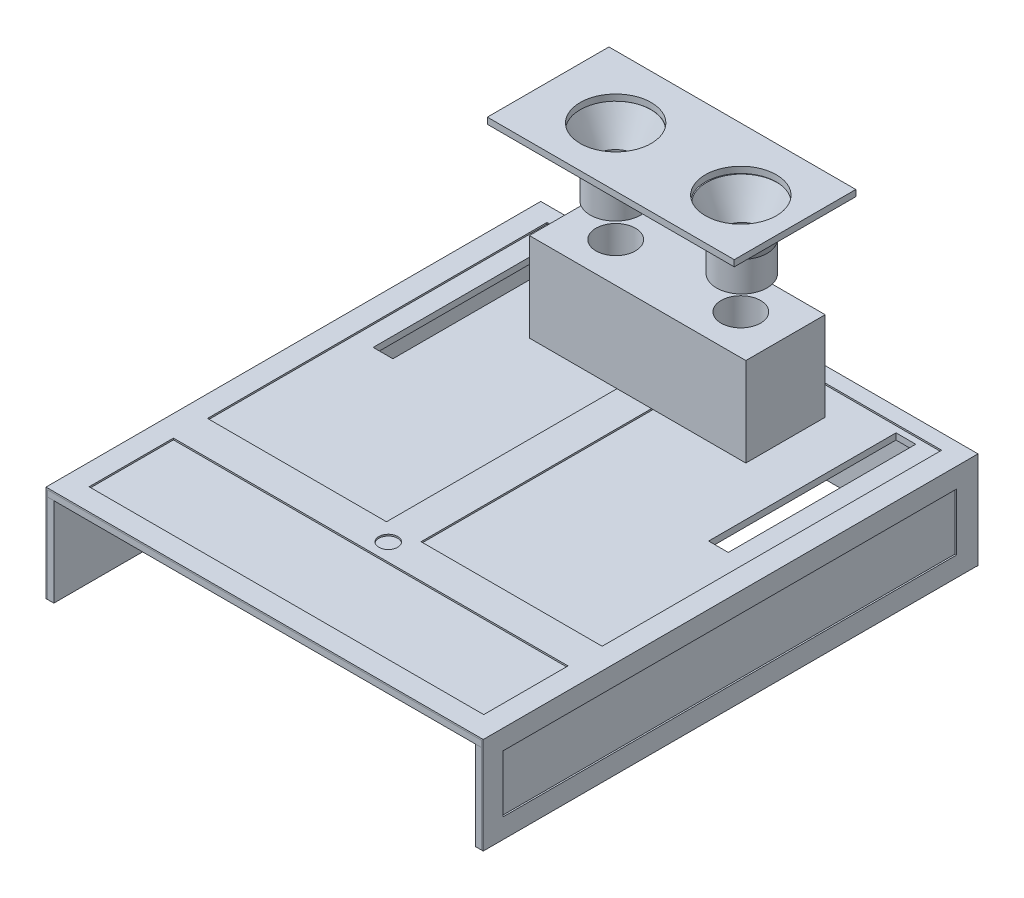
SolidWorks part; units mm, degrees
ref_plane "Front Plane" through (0, 0, 0) normal (0, 0, 1) x (1, 0, 0)
ref_plane "Top Plane" through (0, 0, 0) normal (0, 1, 0) x (1, 0, 0)
ref_plane "Right Plane" through (0, 0, 0) normal (1, 0, 0) x (0, 0, -1)
sketch "Sketch2" plane through (0, 0, 0) normal (0, 1, 0) x (1, 0, 0)
  line L7 (-162.2662, -88.2141) -> (57.7338, -88.2141)
  line L8 (27.7338, 151.7859) -> (37.7338, 151.7859)
  line L9 (57.7338, -88.2141) -> (57.7338, -68.2141)
  line L10 (57.7338, -68.2141) -> (54.5588, -68.2141)
  line L11 (54.5588, -68.2141) -> (54.5588, -48.2141)
  line L12 (54.5588, -48.2141) -> (57.7338, -48.2141)
  line L13 (-162.2662, -88.2141) -> (-162.2662, -68.2141)
  line L14 (-162.2662, -68.2141) -> (-159.0912, -68.2141)
  line L15 (-159.0912, -68.2141) -> (-159.0912, -48.2141)
  line L16 (-159.0912, -48.2141) -> (-162.2662, -48.2141)
  line L17 (-162.2662, -48.2141) -> (-162.2662, -28.2141)
  line L18 (-162.2662, -28.2141) -> (-159.0912, -28.2141)
  line L19 (-159.0912, -28.2141) -> (-159.0912, -8.2141)
  line L20 (-159.0912, -8.2141) -> (-162.2662, -8.2141)
  line L21 (57.7338, -28.2141) -> (54.5588, -28.2141)
  line L22 (54.5588, -28.2141) -> (54.5588, -8.2141)
  line L23 (54.5588, -8.2141) -> (57.7338, -8.2141)
  line L24 (57.7338, -48.2141) -> (57.7338, -28.2141)
  line L25 (-162.2662, -8.2141) -> (-162.2662, 11.7859)
  line L26 (-162.2662, 11.7859) -> (-159.0912, 11.7859)
  line L27 (-159.0912, 11.7859) -> (-159.0912, 31.7859)
  line L28 (-159.0912, 31.7859) -> (-162.2662, 31.7859)
  line L29 (57.7338, 11.7859) -> (54.5588, 11.7859)
  line L30 (54.5588, 11.7859) -> (54.5588, 31.7859)
  line L31 (54.5588, 31.7859) -> (57.7338, 31.7859)
  line L32 (57.7338, -8.2141) -> (57.7338, 11.7859)
  line L33 (-162.2662, 31.7859) -> (-162.2662, 51.7859)
  line L34 (-162.2662, 51.7859) -> (-159.0912, 51.7859)
  line L35 (-159.0912, 51.7859) -> (-159.0912, 71.7859)
  line L36 (-159.0912, 71.7859) -> (-162.2662, 71.7859)
  line L37 (57.7338, 51.7859) -> (54.5588, 51.7859)
  line L38 (54.5588, 51.7859) -> (54.5588, 71.7859)
  line L39 (54.5588, 71.7859) -> (57.7338, 71.7859)
  line L40 (57.7338, 31.7859) -> (57.7338, 51.7859)
  line L45 (27.7338, 151.7859) -> (27.7338, 56.7859)
  line L46 (27.7338, 56.7859) -> (37.7338, 56.7859)
  line L47 (37.7338, 151.7859) -> (37.7338, 56.7859)
  line L48 (-142.2662, 151.7859) -> (-132.2662, 151.7859)
  line L49 (-142.2662, 151.7859) -> (-142.2662, 56.7859)
  line L50 (-142.2662, 56.7859) -> (-132.2662, 56.7859)
  line L51 (-132.2662, 151.7859) -> (-132.2662, 56.7859)
  line L52 (-162.2662, 71.7859) -> (-162.2662, 91.7859)
  line L53 (-162.2662, 91.7859) -> (-159.0912, 91.7859)
  line L54 (-159.0912, 91.7859) -> (-159.0912, 111.7859)
  line L55 (-159.0912, 111.7859) -> (-162.2662, 111.7859)
  line L56 (57.7338, 91.7859) -> (54.5588, 91.7859)
  line L57 (54.5588, 91.7859) -> (54.5588, 111.7859)
  line L58 (54.5588, 111.7859) -> (57.7338, 111.7859)
  line L59 (57.7338, 71.7859) -> (57.7338, 91.7859)
  line L63 (-162.2662, 111.7859) -> (-162.2662, 131.7859)
  line L64 (-162.2662, 131.7859) -> (-159.0912, 131.7859)
  line L65 (-159.0912, 131.7859) -> (-159.0912, 151.7859)
  line L66 (-159.0912, 151.7859) -> (-162.2662, 151.7859)
  line L67 (57.7338, 131.7859) -> (54.5588, 131.7859)
  line L68 (54.5588, 131.7859) -> (54.5588, 151.7859)
  line L69 (54.5588, 151.7859) -> (57.7338, 151.7859)
  line L70 (57.7338, 111.7859) -> (57.7338, 131.7859)
  line L71 (57.7338, 151.7859) -> (57.7338, 161.7859)
  line L72 (57.7338, 161.7859) -> (-162.2662, 161.7859)
  line L73 (-162.2662, 161.7859) -> (-162.2662, 151.7859)
  dimension "D1" = 3.175
  dimension "D2" = 20
  dimension "D3" = 20
  dimension "D4" = 3.175
  dimension "D6" = 220
  dimension "D8" = 10
  dimension "D9" = 10
  dimension "D10" = 20
  dimension "D11" = 20
  dimension "D13" = 95
  dimension "D7" = 10
  dimension "D12" = 10
  dimension "D5" = 6
extrude "Boss-Extrude1" add sketch "Sketch2" along normal blind 3.175
sketch "Sketch3" plane through (-159.0912, 0, 0) normal (-1, 0, 0) x (0, 0, 1)
  line L0 (68.2141, 3.175) -> (68.2141, 0)
  line L1 (68.2141, 0) -> (88.2141, 0)
  line L2 (88.2141, 0) -> (88.2141, -45)
  line L3 (68.2141, 3.175) -> (48.2141, 3.175)
  line L4 (48.2141, 3.175) -> (48.2141, 0)
  line L5 (48.2141, 0) -> (28.2141, 0)
  line L6 (28.2141, 0) -> (28.2141, 3.175)
  line L7 (28.2141, 3.175) -> (8.2141, 3.175)
  line L8 (8.2141, 3.175) -> (8.2141, 0)
  line L9 (8.2141, 0) -> (-11.7859, 0)
  line L10 (-11.7859, 0) -> (-11.7859, 3.175)
  line L11 (-91.7859, 0) -> (-91.7859, 3.175)
  line L12 (-11.7859, 3.175) -> (-31.7859, 3.175)
  line L13 (-31.7859, 3.175) -> (-31.7859, 0)
  line L14 (-31.7859, 0) -> (-51.7859, 0)
  line L15 (-51.7859, 0) -> (-51.7859, 3.175)
  line L16 (-51.7859, 3.175) -> (-71.7859, 3.175)
  line L17 (-71.7859, 3.175) -> (-71.7859, 0)
  line L18 (-71.7859, 0) -> (-91.7859, 0)
  line L21 (-91.7859, 3.175) -> (-111.7859, 3.175)
  line L22 (-111.7859, 3.175) -> (-111.7859, 0)
  line L25 (-111.7859, 0) -> (-131.7859, 0)
  line L26 (-151.7859, 0) -> (-131.7859, 0) construction
  line L27 (-131.7859, 3.175) -> (-131.7859, 0) construction
  line L28 (-131.7859, 0) -> (-131.7859, 3.175)
  line L29 (-131.7859, 3.175) -> (-151.7859, 3.175)
  line L30 (-151.7859, 3.175) -> (-151.7859, 0)
  line L31 (-151.7859, 3.175) -> (-151.7859, 0) construction
  line L32 (-151.7859, 0) -> (-161.732, 0)
  line L33 (-161.732, 0) -> (-161.732, -45)
  line L34 (-161.732, -45) -> (88.2141, -45)
extrude "Boss-Extrude2" add sketch "Sketch3" along normal blind 3.175 separate body
sketch "Sketch6" plane through (0, 3.175, 0) normal (0, 1, 0) x (1, 0, 0)
  line L21 (57.7338, 161.7859) -> (57.7338, -88.2141)
  line L23 (57.7338, -88.2141) -> (-162.2662, -88.2141)
  line L25 (-162.2662, -88.2141) -> (-162.2662, 161.7859)
  line L27 (-162.2662, 161.7859) -> (57.7338, 161.7859)
  line L28 (57.7338, 111.7859) -> (57.7338, 131.7859) construction
  line L29 (57.7338, 161.7859) -> (-162.2662, 161.7859) construction
  line L30 (-152.2662, -77.1624) -> (47.7338, -77.1624)
  line L36 (-162.2662, -88.2141) -> (57.7338, -88.2141) construction
  line L37 (-61.5425, 154.9088) -> (-152.2662, 154.9088)
  line L38 (-162.2662, 51.7859) -> (-162.2662, 31.7859) construction
  line L39 (-152.2662, -77.1624) -> (-152.2662, -34.4256)
  line L40 (-152.2662, -34.4256) -> (47.7338, -34.4256)
  line L41 (47.7338, -77.1624) -> (47.7338, -34.4256)
  line L43 (-152.2662, 154.9088) -> (-152.2662, -17.1634)
  line L44 (-152.2662, -17.1634) -> (-61.5425, -17.1634)
  line L46 (-44.0444, -17.1634) -> (47.7338, -17.1634)
  line L47 (-44.0444, -17.1634) -> (-44.0444, 154.9088)
  line L48 (-44.0444, 154.9088) -> (47.7338, 154.9088)
  line L49 (47.7338, -17.1634) -> (47.7338, 154.9088)
  line L50 (-61.5425, 154.9088) -> (-61.5425, -17.1634)
  circle A0 centre (-52.2662, -25.5384) radius 4.757
extrude "Boss-Extrude5" add sketch "Sketch6" along normal blind 0.8 separate body
sketch "Sketch9" plane through (-162.2662, 0, 0) normal (-1, 0, 0) x (0, 0, 1)
  line L0 (-161.732, 3.975) -> (-161.732, -45)
  line L1 (-161.732, -45) -> (88.2141, -45)
  line L2 (88.2141, -45) -> (88.2141, 3.975)
  line L3 (88.2141, 3.975) -> (-161.732, 3.975)
  line L4 (78.2141, -6.025) -> (-151.732, -6.025)
  line L5 (-151.732, -6.025) -> (-151.732, -35)
  line L6 (-151.732, -35) -> (78.2141, -35)
  line L7 (78.2141, -35) -> (78.2141, -6.025)
  line L8 (-161.732, 0) -> (-161.732, -45) construction
extrude "Boss-Extrude7" add sketch "Sketch9" along normal blind 0.8
ref_plane "Plane3" through (-52.2662, 0, 0) normal (-1, 0, 0) x (0, 0, 1)
sketch "Sketch10" plane through (0, 3.975, 0) normal (0, 1, 0) x (1, 0, 0)
  line L0 (3.7439, 139.8898) -> (-105.9534, 139.8898)
  line L1 (3.7439, 139.8898) -> (3.7439, 99.6617)
  line L2 (-105.9534, 139.8898) -> (-105.9534, 99.6617)
  line L3 (3.7439, 99.6617) -> (-105.9534, 99.6617)
extrude "Boss-Extrude8" add sketch "Sketch10" along normal blind 45 separate body
sketch "Sketch11" plane through (0, 48.975, 0) normal (0, 1, 0) x (1, 0, 0)
  circle A1 centre (-82.3327, 119.7757) radius 10
  circle A2 centre (-18.9098, 119.7757) radius 10
extrude "Cut-Extrude1" cut sketch "Sketch11" against normal blind 30
sketch "Sketch12" plane through (0, 3.975, 0) normal (0, 1, 0) x (1, 0, 0)
  circle A0 centre (-113.3178, 147.3993) radius 3.4149
extrude "Boss-Extrude9" add sketch "Sketch12" along normal blind 93 separate body
sketch "Sketch13" plane through (0, 96.975, 0) normal (0, 1, 0) x (1, 0, 0)
  line L0 (-117.4222, 151.4397) -> (7.7034, 151.4397)
  line L1 (-117.4222, 151.4397) -> (-117.4222, 89.8269)
  line L2 (7.7034, 151.4397) -> (7.7034, 89.8269)
  line L3 (-117.4222, 89.8269) -> (7.7034, 89.8269)
  circle A0 centre (-82.3327, 119.7757) radius 18
  circle A2 centre (-18.9098, 119.7757) radius 18
extrude "Boss-Extrude10" add sketch "Sketch13" along normal blind 3.175
ref_plane "Plane1" through (-82.4222, 0, 0) normal (1, 0, 0) x (0, 0, -1)
sketch "Sketch14" plane through (-82.4222, 0, 0) normal (1, 0, 0) x (0, 0, -1)
  line L0 (101.834, 96.975) -> (109.6255, 81.2515)
  line L1 (89.8269, 96.975) -> (151.4397, 96.975) construction
  line L2 (109.6255, 81.2515) -> (106.9626, 81.2515)
  line L3 (106.9626, 81.2515) -> (99.3429, 96.975)
  line L4 (99.3429, 96.975) -> (101.834, 96.975)
  line L5 (119.7757, 48.975) -> (119.7757, 121.3419) construction
  line L6 (99.6617, 48.975) -> (139.8898, 48.975) construction
revolve "Revolve1" add sketch "Sketch14" angle 360 about L5
ref_plane "Plane2" through (-50.4222, 0, 0) normal (-1, 0, 0) x (0, 0, 1)
sketch "Sketch16" plane through (0, 81.2515, 0) normal (0, -1, 0) x (1, 0, 0)
  circle A2 centre (-82.4222, -119.7757) radius 10.2644
  circle A3 centre (-82.4222, -119.7757) radius 12.8132
extrude "Boss-Extrude11" add sketch "Sketch16" along normal blind 15.175
mirror "Mirror2" about plane through (-50.4222, 0, 0) normal (-1, 0, 0) of "Boss-Extrude11", "Revolve1"
mirror "Mirror4" about plane through (-52.2662, 0, 0) normal (-1, 0, 0) of bodies 103
mirror "Mirror5" about plane through (-52.2662, 0, 0) normal (-1, 0, 0) of "Boss-Extrude7"
sketch "Sketch17" plane through (0, 0, -161.732) normal (0, 0, -1) x (-1, 0, 0)
  line L0 (-58.5338, 3.975) -> (163.0662, 3.975)
  line L1 (-58.5338, 3.975) -> (-58.5338, -45.1595)
  line L2 (163.0662, 3.975) -> (163.0662, -45.1595)
  line L3 (-58.5338, -45.1595) -> (163.0662, -45.1595)
extrude "Boss-Extrude12" add sketch "Sketch17" along normal blind 0.8
equation "\"hardboard_width\"= 3.175"
equation "\"D1@Boss-Extrude1\"=\"hardboard_width\""
equation "\"D1@Sketch2\"=\"hardboard_width\""
equation "\"D4@Sketch2\"=\"hardboard_width\""
equation "\"D1@Boss-Extrude2\"=\"hardboard_width\""
equation "\"steel_24g_thickness\"= 0.8"
equation "\"D1@Boss-Extrude5\"=\"steel_24g_thickness\""
equation "\"D1@Boss-Extrude7\"=\"steel_24g_thickness\""
equation "\"D1@Boss-Extrude10\"=\"hardboard_width\""
equation "\"D1@Boss-Extrude12\"=\"steel_24g_thickness\""
